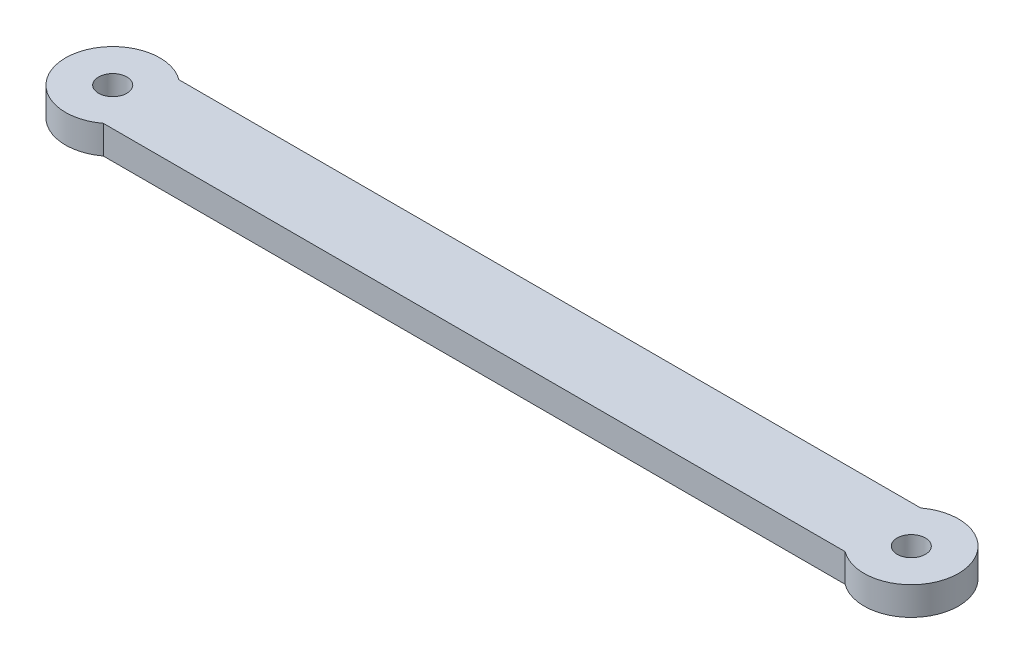
SolidWorks part; units mm, degrees
ref_plane "Alzado" through (0, 0, 0) normal (0, 0, 1) x (1, 0, 0)
ref_plane "Planta" through (0, 0, 0) normal (0, 1, 0) x (1, 0, 0)
ref_plane "Vista lateral" through (0, 0, 0) normal (1, 0, 0) x (0, 0, -1)
sketch "Croquis1" plane through (0, 0, 0) normal (0, 1, 0) x (1, 0, 0)
  line L0 (-39.2681, 4) -> (39.268, 4)
  line L2 (39.2681, -4) -> (-39.2681, -4)
  circle A0 centre (-42.2681, 0) radius 1.5
  arc A1 (-39.2681, 4) -> (-39.2681, -4) centre (-42.2681, 0) ccw
  circle A2 centre (42.2681, 0) radius 1.5
  arc A3 (39.268, 4) -> (39.2681, -4) centre (42.2681, 0) cw
  dimension "D1" = 3
  dimension "D2" = 10
  dimension "D6" = 5
  dimension "D9" = 3
  dimension "D3" = 4
  dimension "D4" = 4
  dimension "D5" = 84.5361
  dimension "D7" = 42.2681
extrude "Saliente-Extruir1" add sketch "Croquis1" along normal blind 3
